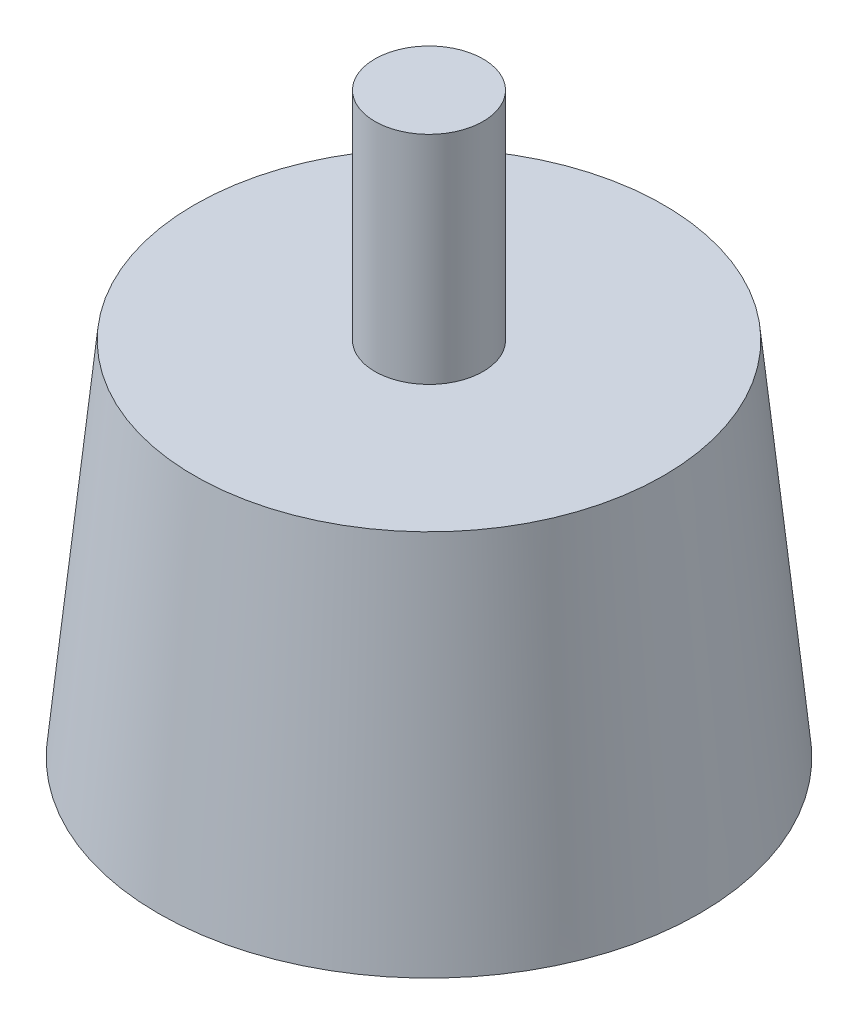
SolidWorks part; units mm, degrees
ref_plane "Front Plane" through (0, 0, 0) normal (0, 0, 1) x (1, 0, 0)
ref_plane "Top Plane" through (0, 0, 0) normal (0, 1, 0) x (1, 0, 0)
ref_plane "Right Plane" through (0, 0, 0) normal (1, 0, 0) x (0, 0, -1)
sketch "Sketch1" plane through (0, 0, 0) normal (0, 0, 1) x (1, 0, 0)
  line L0 (0, 0) -> (15, 0)
  line L1 (15, 0) -> (13, 20)
  line L2 (13, 20) -> (3, 20)
  line L3 (3, 20) -> (3, 32)
  line L4 (3, 32) -> (0, 32)
  line L5 (0, 32) -> (0, 0)
  dimension "D1" = 3
  dimension "D2" = 20
  dimension "D3" = 15
  dimension "D4" = 12
  dimension "D5" = 10
revolve "Revolve1" add sketch "Sketch1" angle 360 about L5
